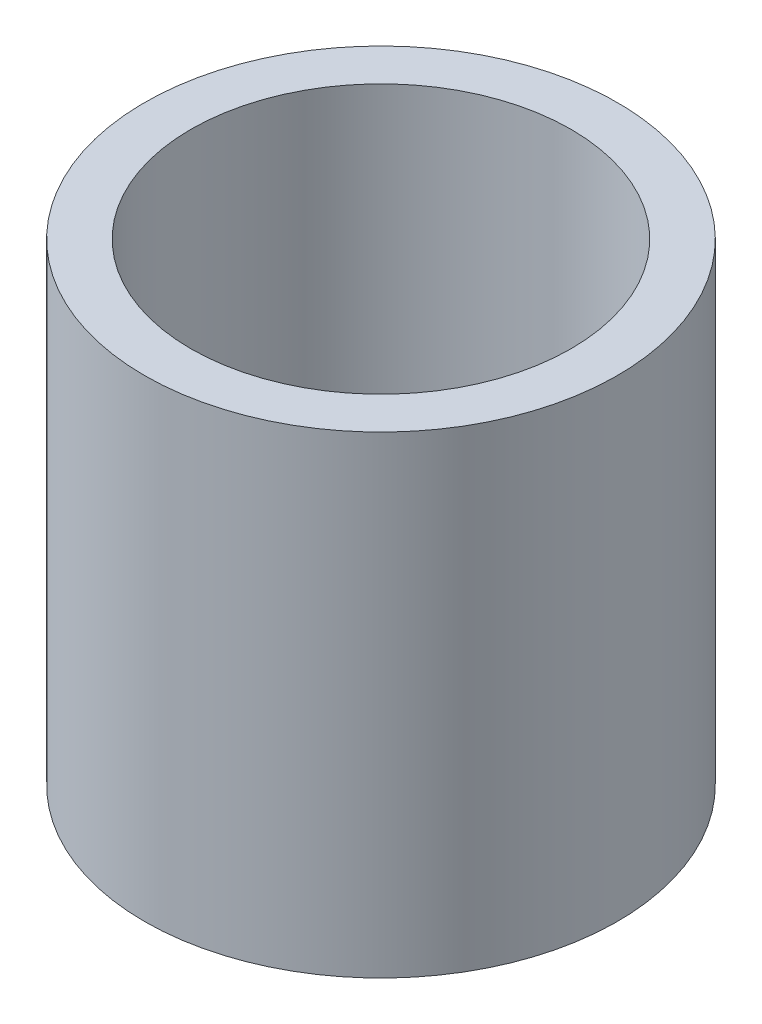
SolidWorks part; units mm, degrees
material "Cast Alloy Steel"
ref_plane "Front Plane" through (0, 0, 0) normal (0, 0, 1) x (1, 0, 0)
ref_plane "Top Plane" through (0, 0, 0) normal (0, 1, 0) x (1, 0, 0)
ref_plane "Right Plane" through (0, 0, 0) normal (1, 0, 0) x (0, 0, -1)
other "Configuration Table"
sketch "Sketch1" plane through (0, 0, 0) normal (0, 1, 0) x (1, 0, 0)
  circle A0 centre (0, 0) radius 3.175
  dimension "D1" = 6.35
extrude "Boss-Extrude1" add sketch "Sketch1" along normal blind 6.35
hole_wizard "1/4-20 Tapped Hole1" positions "Sketch2" profile "Sketch3" tap size "1/4-20" standard "ANSI Inch" end condition through all
sketch "Sketch2" plane through (0, 6.35, 0) normal (0, 1, 0) x (1, 0, 0)
  point P0 (0, 0)
sketch "Sketch3" plane through (0, 6.35, 0) normal (1, 0, 0) x (0, 0, 1)
  line L0 (0, 0) -> (0, 6.35)
  line L1 (0, 6.35) -> (2.5527, 6.35)
  line L2 (2.5527, 6.35) -> (2.5527, 0)
  line L5 (2.5527, 0) -> (0, 0)
  line L11 (0, -6.35) -> (0, 107.95) construction
  dimension "Thru Tap Drill Dia." = 5.1054
  dimension "Thru Tap Drill Depth" = 6.35
cosmetic thread "Hole Thread1" parameters "D2"=6.35
